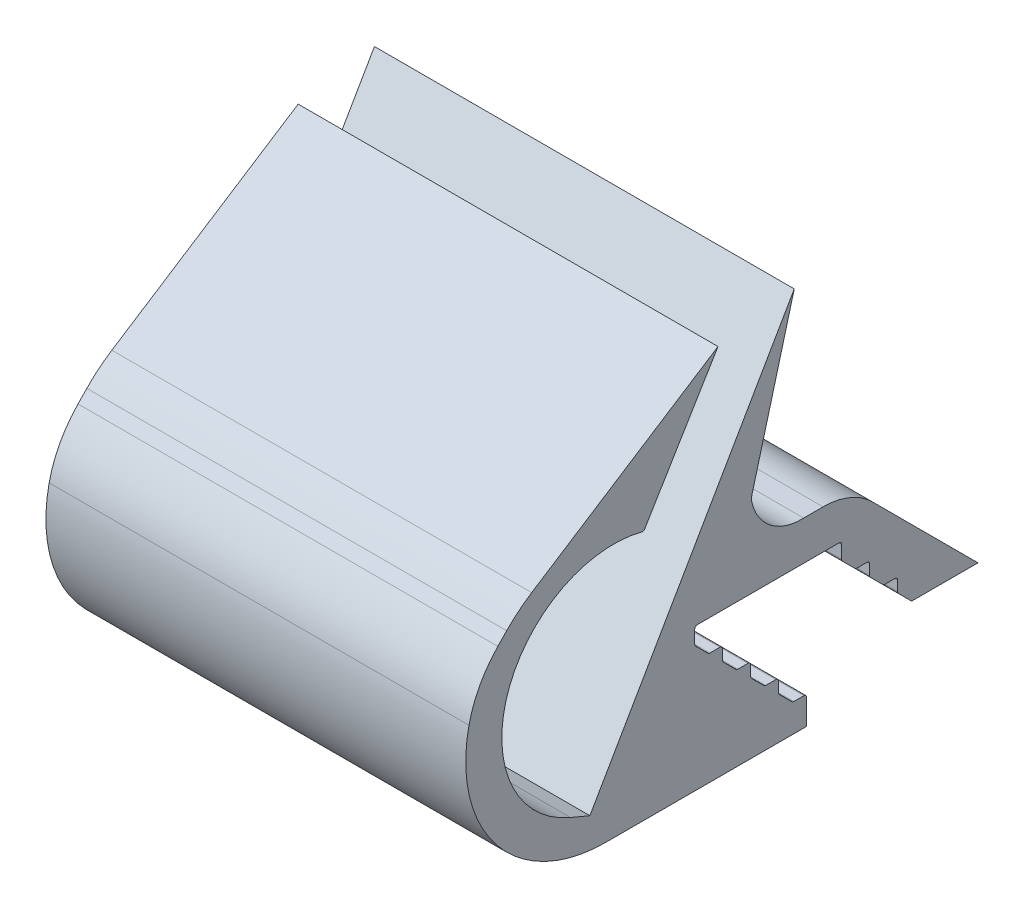
SolidWorks part; units mm, degrees
ref_plane "Front Plane" through (0, 0, 0) normal (0, 0, 1) x (1, 0, 0)
ref_plane "Top Plane" through (0, 0, 0) normal (0, 1, 0) x (1, 0, 0)
ref_plane "Right Plane" through (0, 0, 0) normal (1, 0, 0) x (0, 0, -1)
sketch "Sketch1" plane through (0, 0, 0) normal (1, 0, 0) x (0, 0, -1)
  line L0 (-25.7423, -27.6038) -> (-25.7423, -25.8038)
  line L1 (-25.9423, -25.6038) -> (-26.6594, -25.6038)
  line L9 (-28.8009, -23.5453) -> (-29.6837, -22.6624)
  line L11 (-30.8009, -21.5453) -> (-31.6837, -20.6624)
  line L12 (-27.7423, -24.521) -> (-27.7423, -23.8038)
  line L14 (-18.2421, -23.6035) -> (-19.1835, -22.662)
  line L15 (-27.9423, -23.6038) -> (-28.6594, -23.6038)
  line L16 (-29.7423, -22.521) -> (-29.7423, -21.8038)
  line L19 (-31.9423, -19.6038) -> (-32.6594, -19.6038)
  line L20 (-33.7423, -18.521) -> (-33.7423, -17.6038)
  line L21 (-31.7423, -20.521) -> (-31.7423, -19.8038)
  line L22 (-29.9423, -21.6038) -> (-30.6594, -21.6038)
  line L24 (-17.7421, -23.6035) -> (-18.2421, -23.6035)
  line L25 (-26.8009, -25.5453) -> (-27.6837, -24.6624)
  line L26 (-32.8009, -19.5453) -> (-33.6837, -18.6624)
  line L27 (-23.2423, -18.521) -> (-23.2423, -17.6038)
  line L28 (-19.4421, -21.6038) -> (-20.1594, -21.6038)
  line L29 (-20.3009, -21.5453) -> (-21.1837, -20.6624)
  line L30 (-22.3009, -19.5453) -> (-23.1837, -18.6624)
  line L31 (-21.2423, -20.521) -> (-21.2423, -19.8038)
  line L32 (-21.4423, -19.6038) -> (-22.1594, -19.6038)
  line L33 (-19.2421, -22.5206) -> (-19.2421, -21.8038)
  line L38 (-28.3609, -3.0868) -> (-41.2339, -25.3835)
  line L39 (-13.4995, -23.6035) -> (-17.7421, -23.6035)
  line L42 (-47.8111, -11.6166) -> (-47.1811, -10.9647)
  line L47 (-25.9603, -14.6035) -> (-24.5705, -14.6035)
  line L55 (-26.6289, -0.0868) -> (-28.3609, -3.0868)
  line L58 (-26.6289, -0.0868) -> (-29.648, -11.293)
  line L61 (-40.1051, -27.6038) -> (-25.7423, -27.6038)
  line L63 (-21.035, -16.0679) -> (-13.4995, -23.6035)
  line L66 (-41.2339, -25.3835) -> (-42.6155, -24.805)
  line L67 (-45.3935, -9.4996) -> (-32.0786, -0.9261)
  line L70 (-32.0786, -0.9261) -> (-37.3085, -9.5846)
  line L71 (-33.5423, -17.4038) -> (-23.4423, -17.4038)
  arc A1 (-37.5316, -9.6783) -> (-42.6155, -24.805) centre (-39.5261, -17.4256) ccw
  arc A2 (-40.1051, -27.6038) -> (-49.8742, -15.467) centre (-40.1051, -17.6038) cw
  arc A3 (-47.8111, -11.6166) -> (-49.8742, -15.467) centre (-42.0589, -17.1765) ccw
  arc A10 (-47.1811, -10.9647) -> (-45.3935, -9.4996) centre (-39.9909, -17.9146) cw
  arc A14 (-29.6584, -11.7711) -> (-25.9603, -14.6035) centre (-26.1191, -10.9805) ccw
  arc A16 (-24.5705, -14.6035) -> (-21.035, -16.0679) centre (-24.5705, -19.6035) cw
  arc A17 (-29.6584, -11.7711) -> (-29.648, -11.293) centre (-28.6824, -11.5531) cw
  arc A18 (-37.3085, -9.5846) -> (-37.5316, -9.6783) centre (-37.4817, -9.4846) cw
  arc A19 (-19.4421, -21.6038) -> (-19.2421, -21.8038) centre (-19.4421, -21.8038) cw
  arc A20 (-23.2423, -17.6038) -> (-23.4423, -17.4038) centre (-23.4423, -17.6038) ccw
  arc A21 (-21.2423, -19.8038) -> (-21.4423, -19.6038) centre (-21.4423, -19.8038) ccw
  arc A22 (-25.7423, -25.8038) -> (-25.9423, -25.6038) centre (-25.9423, -25.8038) ccw
  arc A23 (-27.7423, -23.8038) -> (-27.9423, -23.6038) centre (-27.9423, -23.8038) ccw
  arc A24 (-29.7423, -21.8038) -> (-29.9423, -21.6038) centre (-29.9423, -21.8038) ccw
  arc A25 (-31.7423, -19.8038) -> (-31.9423, -19.6038) centre (-31.9423, -19.8038) ccw
  arc A26 (-33.7423, -17.6038) -> (-33.5423, -17.4038) centre (-33.5423, -17.6038) cw
  arc A27 (-23.2423, -18.521) -> (-23.1837, -18.6624) centre (-23.0423, -18.521) ccw
  arc A28 (-22.3009, -19.5453) -> (-22.1594, -19.6038) centre (-22.1594, -19.4038) ccw
  arc A29 (-21.1837, -20.6624) -> (-21.2423, -20.521) centre (-21.0423, -20.521) cw
  arc A30 (-20.1594, -21.6038) -> (-20.3009, -21.5453) centre (-20.1594, -21.4038) cw
  arc A31 (-19.1835, -22.662) -> (-19.2421, -22.5206) centre (-19.0421, -22.5206) cw
  arc A32 (-26.6594, -25.6038) -> (-26.8009, -25.5453) centre (-26.6594, -25.4038) cw
  arc A33 (-27.6837, -24.6624) -> (-27.7423, -24.521) centre (-27.5423, -24.521) cw
  arc A34 (-28.8009, -23.5453) -> (-28.6594, -23.6038) centre (-28.6594, -23.4038) ccw
  arc A35 (-29.6837, -22.6624) -> (-29.7423, -22.521) centre (-29.5423, -22.521) cw
  arc A36 (-30.6594, -21.6038) -> (-30.8009, -21.5453) centre (-30.6594, -21.4038) cw
  arc A37 (-31.6837, -20.6624) -> (-31.7423, -20.521) centre (-31.5423, -20.521) cw
  arc A38 (-32.6594, -19.6038) -> (-32.8009, -19.5453) centre (-32.6594, -19.4038) cw
  arc A39 (-33.6837, -18.6624) -> (-33.7423, -18.521) centre (-33.5423, -18.521) cw
  point P6 (-49.2365, -13.4198)
  dimension "D1" = 10
  dimension "D2" = 8
  dimension "D3" = 5
  dimension "D4" = 10
  dimension "D5" = 1
  dimension "D6" = 0.2
  dimension "D7" = 0.2
  dimension "D8" = 0.2
  dimension "D9" = 0.2
extrude "Boss-Extrude1" add sketch "Sketch1" along normal blind 100
sketch "Sketch2" plane through (76.9789, -34.994, 31.934) normal (0, 0, 1) x (1, 0, 0)
  line L3 (-46.9789, 36.8427) -> (-6.9789, 36.8427)
  line L6 (-46.9789, -2.227) -> (-6.9789, -2.227)
  line L7 (-6.9789, -2.227) -> (-6.9789, 36.8427)
  line L8 (-46.9789, 36.8427) -> (-84.5469, 36.8427)
  line L9 (-84.5469, 36.8427) -> (-84.5469, -2.227)
  line L10 (-84.5469, -2.227) -> (-46.9789, -2.227)
  point P0 (-26.9789, 34.2825)
extrude "Cut-Extrude1" cut sketch "Sketch2" against normal blind 23 and the other way blind 25
